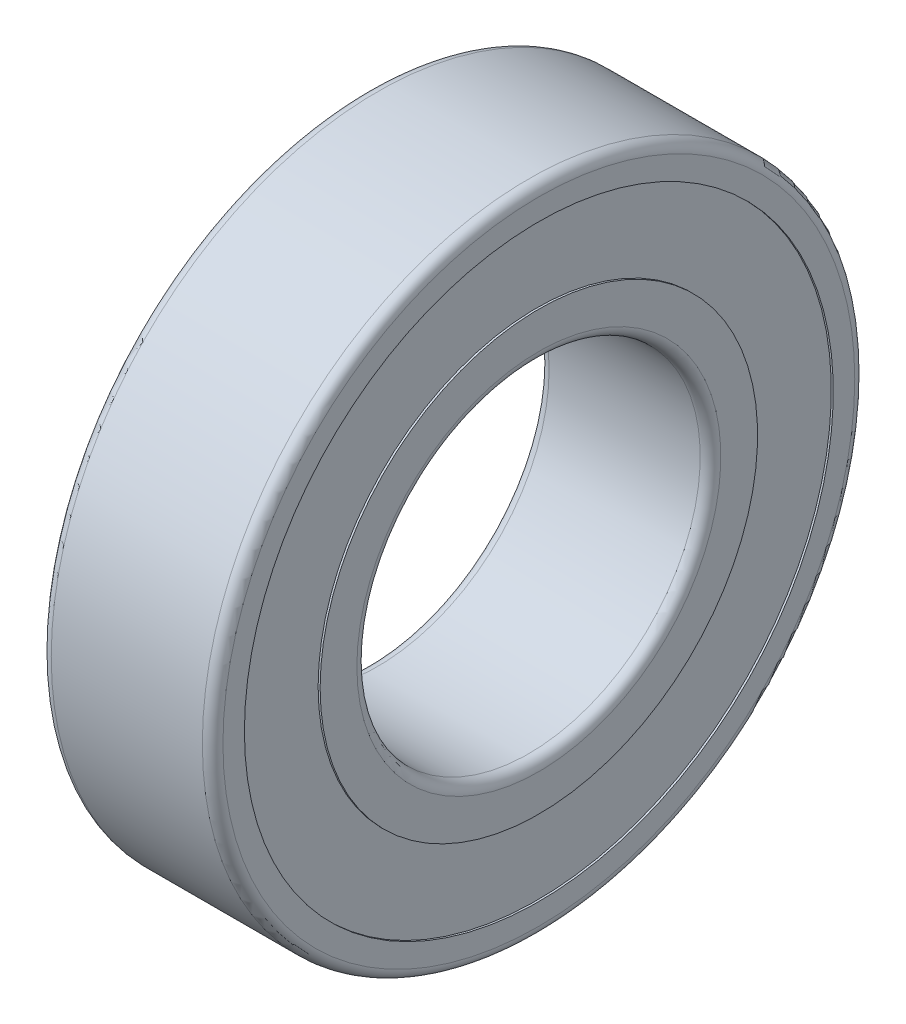
SolidWorks part; units mm, degrees
material "炭素鋼(普通)"
ref_plane "Front Plane" through (0, 0, 0) normal (0, 0, 1) x (1, 0, 0)
ref_plane "Top Plane" through (0, 0, 0) normal (0, 1, 0) x (1, 0, 0)
ref_plane "Right Plane" through (0, 0, 0) normal (1, 0, 0) x (0, 0, -1)
sketch "Sketch1" plane through (0, 0, 0) normal (0, 0, 1) x (1, 0, 0)
  line L0 (0, 0) -> (5, 0) construction
  line L1 (0, 5) -> (5, 5)
  line L2 (0, 9.5) -> (5, 9.5)
  line L3 (0, 9.5) -> (0, 8.575)
  line L4 (0, 8.575) -> (0.058, 8.575)
  line L5 (5, 9.5) -> (5, 8.575)
  line L6 (0.058, 8.575) -> (0.058, 6.37)
  line L7 (0.058, 6.37) -> (0, 6.37)
  line L8 (0, 6.37) -> (0, 5)
  line L9 (5, 8.575) -> (4.942, 8.575)
  line L10 (4.942, 8.575) -> (4.942, 6.37)
  line L11 (4.942, 6.37) -> (5, 6.37)
  line L12 (5, 6.37) -> (5, 5)
  dimension "D" = 19
  dimension "B" = 5
  dimension "D_s" = 10
  dimension "MSM_1" = 17.15
  dimension "MSM_2" = 12.74
  dimension "MSM_3" = 0.058
revolve "Revolve1" add sketch "Sketch1" angle 360 about L0
fillet "Fillet1" radius 0.3 2 edges at (5, 0, 9.5) (0, 0, 9.5)
fillet "Fillet2" radius 0.3 2 edges at (5, 0, 5) (0, 0, 5)
